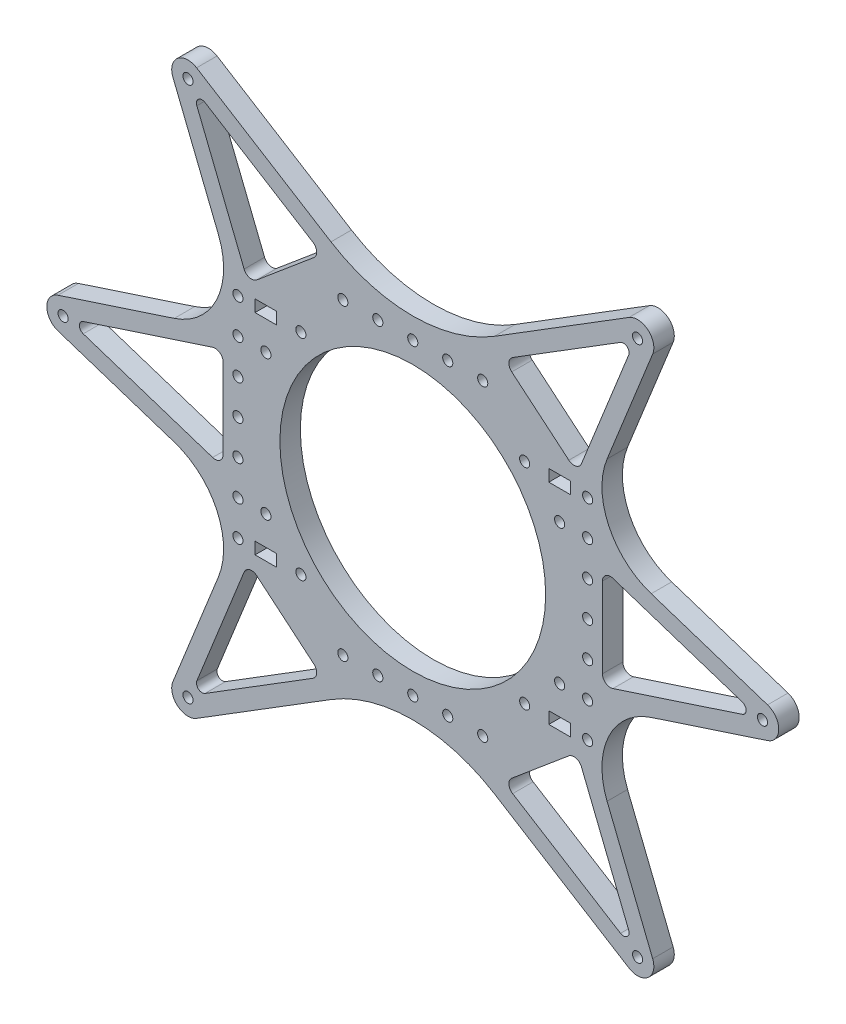
SolidWorks part; units mm, degrees
material "Acrylic (Medium-high impact)"
ref_plane "Front Plane" through (0, 0, 0) normal (0, 0, 1) x (1, 0, 0)
ref_plane "Top Plane" through (0, 0, 0) normal (0, 1, 0) x (1, 0, 0)
ref_plane "Right Plane" through (0, 0, 0) normal (1, 0, 0) x (0, 0, -1)
sketch "Sketch1" plane through (0, 0, 0) normal (0, 0, 1) x (1, 0, 0)
  line L0 (-447622.4345, 422.8828) -> (448935.6268, 422.8828) construction
  line L1 (587.9953, 497.7534) -> (601.0264, 465.2697)
  line L2 (698.5962, 452.8828) -> (698.5962, 392.8828) construction
  line L3 (653.3971, 419.0702) -> (-31485.9834, -37883.1519) construction
  line L4 (701.6962, 394.5828) -> (695.4962, 391.1828) construction
  line L5 (701.6962, 391.1828) -> (695.4962, 394.5828) construction
  line L6 (594.8522, 494.09) -> (608.3693, 460.3949)
  line L7 (594.7755, 503.4426) -> (633.2109, 479.5572)
  line L8 (597.1925, 496.0537) -> (628.0285, 476.8909)
  line L9 (594.8522, 494.09) -> (597.1925, 496.0537) construction
  line L10 (701.6962, 391.1828) -> (695.4962, 391.1828)
  line L11 (695.4962, 394.5828) -> (695.4962, 391.1828)
  line L12 (701.6962, 394.5828) -> (695.4962, 394.5828)
  line L13 (594.7755, 503.4426) -> (587.9953, 497.7534) construction
  line L14 (628.2915, 473.1954) -> (611.963, 459.4942)
  line L15 (608.3693, 460.3949) -> (628.0285, 476.8909) construction
  line L16 (701.6962, 394.5828) -> (701.6962, 391.1828)
  line L17 (-343.4038, 422.8828) -> (49656.5962, 422.8828) construction
  line L18 (648.8948, 432.061) -> (-31490.4849, 38734.2822) construction
  line L19 (-347.3366, 472.8828) -> (49652.6634, 472.8828) construction
  line L20 (-347.2527, 372.8828) -> (49652.7473, 372.8828) construction
  line L21 (562.3601, 421.3552) -> (599.3601, 409.2322)
  line L22 (602.3601, 434.3594) -> (602.3601, 411.4062)
  line L23 (555.1462, 427.3082) -> (555.1462, 418.4573) construction
  line L24 (562.3601, 424.4103) -> (599.3601, 436.5334)
  line L25 (599.3601, 409.2322) -> (599.3601, 436.5334) construction
  line L26 (555.1462, 427.3082) -> (588.4064, 438.2059)
  line L27 (562.3601, 421.3552) -> (562.3601, 424.4103) construction
  line L28 (555.1462, 418.4573) -> (588.4064, 407.5596)
  line L29 (594.8522, 351.6756) -> (608.3693, 385.3706)
  line L30 (594.7755, 342.3229) -> (633.2109, 366.2084)
  line L31 (611.963, 386.2714) -> (628.2915, 372.5702)
  line L32 (611.4962, 451.1828) -> (617.6962, 454.5828) construction
  line L33 (611.4962, 454.5828) -> (617.6962, 451.1828) construction
  line L34 (597.1925, 349.7118) -> (594.8522, 351.6756) construction
  line L35 (587.9953, 348.0122) -> (594.7755, 342.3229) construction
  line L36 (628.0285, 368.8746) -> (608.3693, 385.3706) construction
  line L37 (597.1925, 349.7118) -> (628.0285, 368.8746)
  line L38 (587.9953, 348.0122) -> (601.0264, 380.4959)
  line L39 (611.4962, 391.1828) -> (617.6962, 394.5828) construction
  line L40 (701.6962, 454.5828) -> (695.4962, 451.1828) construction
  line L41 (611.4962, 394.5828) -> (617.6962, 391.1828) construction
  line L42 (614.5962, 452.8828) -> (614.5962, 392.8828) construction
  line L43 (701.6962, 451.1828) -> (695.4962, 454.5828) construction
  line L44 (685.1639, 368.8746) -> (704.8231, 385.3706) construction
  line L45 (725.1971, 348.0122) -> (718.4169, 342.3229) construction
  line L46 (715.9998, 349.7118) -> (718.3402, 351.6756) construction
  line L47 (750.8323, 421.3552) -> (750.8323, 424.4103) construction
  line L48 (713.8323, 409.2322) -> (713.8323, 436.5334) construction
  line L49 (758.0462, 427.3082) -> (758.0462, 418.4573) construction
  line L50 (704.8231, 460.3949) -> (685.1639, 476.8909) construction
  line L51 (718.4169, 503.4426) -> (725.1971, 497.7534) construction
  line L52 (718.3402, 494.09) -> (715.9998, 496.0537) construction
  line L53 (611.4962, 454.5828) -> (617.6962, 454.5828)
  line L54 (617.6962, 451.1828) -> (617.6962, 454.5828)
  line L55 (611.4962, 451.1828) -> (617.6962, 451.1828)
  line L56 (701.6962, 451.1828) -> (701.6962, 454.5828)
  line L57 (701.6962, 451.1828) -> (695.4962, 451.1828)
  line L58 (695.4962, 451.1828) -> (695.4962, 454.5828)
  line L59 (701.6962, 454.5828) -> (695.4962, 454.5828)
  line L60 (725.1971, 348.0122) -> (712.166, 380.4959)
  line L61 (715.9998, 349.7118) -> (685.1639, 368.8746)
  line L62 (701.2294, 386.2714) -> (684.9009, 372.5702)
  line L63 (718.4169, 342.3229) -> (679.9814, 366.2084)
  line L64 (718.3402, 351.6756) -> (704.8231, 385.3706)
  line L65 (758.0462, 418.4573) -> (724.786, 407.5596)
  line L66 (758.0462, 427.3082) -> (724.786, 438.2059)
  line L67 (750.8323, 424.4103) -> (713.8323, 436.5334)
  line L68 (710.8323, 434.3594) -> (710.8323, 411.4062)
  line L69 (750.8323, 421.3552) -> (713.8323, 409.2322)
  line L70 (611.4962, 451.1828) -> (611.4962, 454.5828)
  line L71 (684.9009, 473.1954) -> (701.2294, 459.4942)
  line L72 (611.4962, 394.5828) -> (611.4962, 391.1828)
  line L73 (611.4962, 394.5828) -> (617.6962, 394.5828)
  line L74 (617.6962, 394.5828) -> (617.6962, 391.1828)
  line L75 (715.9998, 496.0537) -> (685.1639, 476.8909)
  line L76 (718.4169, 503.4426) -> (679.9814, 479.5572)
  line L77 (718.3402, 494.09) -> (704.8231, 460.3949)
  line L78 (725.1971, 497.7534) -> (712.166, 465.2697)
  line L79 (611.4962, 391.1828) -> (617.6962, 391.1828)
  line L80 (706.5962, 432.8828) -> (698.5962, 432.8828) construction
  line L81 (706.5962, 422.8828) -> (706.5962, 432.8828) construction
  line L82 (656.5962, 378.8828) -> (646.5962, 378.8828) construction
  line L83 (656.5962, 466.8828) -> (646.5962, 466.8828) construction
  line L84 (-50.5106, -284.224) -> (35304.8285, 35071.1151) construction
  line L85 (-50.5106, -284.224) -> (35304.8285, 35071.1151) construction
  line L86 (1363.703, -284.224) -> (-33991.6361, 35071.1151) construction
  line L111 (656.5962, -513.6368) -> (656.5962, 49486.3632) construction
  arc A0 (597.1925, 496.0537) -> (594.8522, 494.09) centre (596.3441, 494.6884) ccw
  arc A1 (587.9953, 497.7534) -> (594.7755, 503.4426) centre (592.3174, 499.4872) cw
  circle A2 centre (592.3174, 499.4872) radius 1.45
  arc A4 (608.3693, 460.3949) -> (611.963, 459.4942) centre (610.4925, 461.2467) ccw
  arc A5 (628.2915, 473.1954) -> (628.0285, 476.8909) centre (626.821, 474.9479) ccw
  circle A6 centre (592.3174, 499.4872) radius 4.6569 construction
  circle A7 centre (706.5962, 432.8828) radius 1.45
  circle A8 centre (706.5962, 442.8828) radius 1.45
  circle A9 centre (706.5962, 452.8828) radius 1.45
  circle A10 centre (706.5962, 392.8828) radius 1.45
  arc A11 (555.1462, 418.4573) -> (555.1462, 427.3082) centre (556.5962, 422.8828) cw
  circle A12 centre (556.5962, 422.8828) radius 1.45
  circle A13 centre (646.5962, 378.8828) radius 1.45
  circle A14 centre (556.5962, 422.8828) radius 4.6569 construction
  arc A15 (562.3601, 424.4103) -> (562.3601, 421.3552) centre (562.8606, 422.8828) ccw
  circle A16 centre (656.5962, 422.8828) radius 38
  circle A18 centre (636.5962, 378.8828) radius 1.45
  arc A19 (602.3601, 434.3594) -> (599.3601, 436.5334) centre (600.0724, 434.3594) ccw
  circle A20 centre (706.5962, 402.8828) radius 1.45
  arc A21 (599.3601, 409.2322) -> (602.3601, 411.4062) centre (600.0724, 411.4062) ccw
  circle A22 centre (656.5962, 466.8828) radius 1.45
  circle A24 centre (592.3174, 346.2783) radius 4.6569 construction
  arc A25 (628.0285, 368.8746) -> (628.2915, 372.5702) centre (626.821, 370.8177) ccw
  arc A27 (594.7755, 342.3229) -> (587.9953, 348.0122) centre (592.3174, 346.2783) cw
  arc A28 (594.8522, 351.6756) -> (597.1925, 349.7118) centre (596.3441, 351.0771) ccw
  arc A29 (611.963, 386.2714) -> (608.3693, 385.3706) centre (610.4925, 384.5189) ccw
  circle A31 centre (592.3174, 346.2783) radius 1.45
  circle A32 centre (706.5962, 412.8828) radius 1.45
  arc A33 (588.4064, 407.5596) -> (601.0264, 380.4959) centre (582.0351, 388.1144) cw
  circle A34 centre (656.5962, 378.8828) radius 1.45
  arc A35 (588.4064, 438.2059) -> (601.0264, 465.2697) centre (582.0351, 457.6512) ccw
  circle A37 centre (698.5962, 442.8828) radius 1.45
  circle A38 centre (698.5962, 402.8828) radius 1.45
  arc A39 (633.2109, 366.2084) -> (656.5962, 372.8828) centre (656.5962, 328.5778) cw
  arc A40 (633.2109, 479.5572) -> (656.5962, 472.8828) centre (656.5962, 517.1878) ccw
  circle A41 centre (720.8749, 346.2783) radius 4.6569 construction
  circle A42 centre (756.5962, 422.8828) radius 4.6569 construction
  circle A44 centre (646.5962, 466.8828) radius 1.45
  circle A45 centre (636.5962, 466.8828) radius 1.45
  circle A46 centre (720.8749, 499.4872) radius 4.6569 construction
  circle A48 centre (676.5962, 466.8828) radius 1.45
  circle A49 centre (666.5962, 466.8828) radius 1.45
  circle A50 centre (706.5962, 422.8828) radius 1.45
  arc A51 (679.9814, 479.5572) -> (656.5962, 472.8828) centre (656.5962, 517.1878) cw
  arc A52 (679.9814, 366.2084) -> (656.5962, 372.8828) centre (656.5962, 328.5778) ccw
  circle A53 centre (688.5962, 452.8828) radius 1.45
  circle A54 centre (688.5962, 392.8828) radius 1.45
  arc A55 (724.786, 438.2059) -> (712.166, 465.2697) centre (731.1572, 457.6512) cw
  arc A56 (724.786, 407.5596) -> (712.166, 380.4959) centre (731.1572, 388.1144) ccw
  circle A57 centre (624.5962, 392.8828) radius 1.45
  circle A58 centre (720.8749, 346.2783) radius 1.45
  arc A59 (701.2294, 386.2714) -> (704.8231, 385.3706) centre (702.6999, 384.5189) cw
  arc A60 (718.3402, 351.6756) -> (715.9998, 349.7118) centre (716.8483, 351.0771) cw
  arc A61 (718.4169, 342.3229) -> (725.1971, 348.0122) centre (720.8749, 346.2783) ccw
  arc A62 (685.1639, 368.8746) -> (684.9009, 372.5702) centre (686.3714, 370.8177) cw
  arc A63 (713.8323, 409.2322) -> (710.8323, 411.4062) centre (713.12, 411.4062) cw
  arc A64 (710.8323, 434.3594) -> (713.8323, 436.5334) centre (713.12, 434.3594) cw
  circle A65 centre (676.5962, 378.8828) radius 1.45
  arc A66 (750.8323, 424.4103) -> (750.8323, 421.3552) centre (750.3318, 422.8828) cw
  circle A67 centre (666.5962, 378.8828) radius 1.45
  circle A68 centre (756.5962, 422.8828) radius 1.45
  arc A69 (758.0462, 418.4573) -> (758.0462, 427.3082) centre (756.5962, 422.8828) ccw
  circle A70 centre (624.5962, 452.8828) radius 1.45
  circle A71 centre (606.5962, 422.8828) radius 1.45
  arc A74 (684.9009, 473.1954) -> (685.1639, 476.8909) centre (686.3714, 474.9479) cw
  arc A75 (704.8231, 460.3949) -> (701.2294, 459.4942) centre (702.6999, 461.2467) cw
  circle A76 centre (720.8749, 499.4872) radius 1.45
  arc A77 (725.1971, 497.7534) -> (718.4169, 503.4426) centre (720.8749, 499.4872) ccw
  arc A78 (715.9998, 496.0537) -> (718.3402, 494.09) centre (716.8483, 494.6884) cw
  circle A79 centre (614.5962, 402.8828) radius 1.45
  circle A80 centre (614.5962, 442.8828) radius 1.45
  circle A81 centre (606.5962, 412.8828) radius 1.45
  circle A83 centre (606.5962, 402.8828) radius 1.45
  circle A84 centre (606.5962, 392.8828) radius 1.45
  circle A85 centre (606.5962, 452.8828) radius 1.45
  circle A86 centre (606.5962, 442.8828) radius 1.45
  circle A87 centre (606.5962, 432.8828) radius 1.45
  circle A279 centre (626.5962, 466.8828) radius 1.45 [skipped]
  circle A282 centre (626.5962, 378.8828) radius 1.45 [skipped]
  circle A283 centre (698.5962, 422.8828) radius 1.45 [skipped]
  circle A284 centre (698.5962, 432.8828) radius 1.45 [skipped]
  circle A285 centre (698.5962, 412.8828) radius 1.45 [skipped]
  point P2 (620.1272, 466.3448)
  point P4 (604.6798, 472.924)
  point P5 (610.6788, 407.5004)
  point P6 (604.4937, 430.5743)
  point P7 (590.1096, 382.987)
  point P9 (656.5962, 422.8828)
  point P10 (592.2236, 451.9603)
  point P12 (560.2236, 451.9603)
  point P13 (615.5787, 412.0526)
  point P15 (596.4648, 452.5325)
  point P16 (593.7956, 519.1439)
  point P18 (562.0153, 451.7438)
  point P19 (589.324, 503.0546)
  point P21 (557.1601, 445.912)
  point P22 (691.7574, 496.0365)
  point P23 (586.2073, 519.1355)
  point P25 (698.5962, 452.8828)
  point P27 (593.4054, 384.161)
  point P31 (706.9167, 384.1702)
  point P32 (709.3005, 386.1481)
  point P33 (712.3266, 520.5499)
  point P34 (710.2125, 451.5766)
  point P37 (593.7956, 519.1439)
  point P38 (704.5328, 382.1922)
  point P40 (675.1867, 401.4708)
  point P41 (685.2778, 409.8289)
  point P43 (705.5495, 376.706)
  point P44 (637.2651, 404.097)
  point P46 (743.1543, 445.9191)
  point P47 (656.5962, 422.8828)
  point P48 (685.1467, 493.2598)
  point P49 (742.2125, 451.5766)
  point P53 (695.1768, 484.8286)
  point P55 (708.8884, 517.1528)
  point P56 (706.5155, 519.1439)
  point P57 (714.1038, 519.1355)
  point P64 (708.6406, 384.393)
  point P66 (665.171, 499.4399)
  point P67 (704.1427, 521.135)
  point P80 (602.3601, 422.8828)
  point P86 (499.5503, 435.3778)
  point P106 (620.1272, 379.4208)
  point P114 (563.3616, 328.8714)
  point P127 (698.5962, 422.8828)
  point P132 (656.5962, 460.8828)
  point P136 (656.5962, 465.4328)
  point P143 (704.687, 438.4721)
  point P145 (738.2906, 448.6533)
  point P146 (704.7346, 451.575)
  point P147 (738.2991, 451.7509)
  point P148 (738.3077, 454.8484)
  point P244 (749.8308, 328.8714)
  point P245 (693.0651, 379.4208)
  point P246 (710.8323, 422.8828)
  point P247 (698.5962, 422.8828)
  point P248 (723.8684, 503.0546)
  point P249 (693.0651, 466.3448)
  dimension "D2" = 2.9
  dimension "D3" = 6.2644
  dimension "D6" = 4
  dimension "D9" = 4
  dimension "D7" = 4
  dimension "D11" = 100
  dimension "D12" = 5
  dimension "D5" = 10
  dimension "D19" = 50
  dimension "D20" = 100
  dimension "D25" = 6.2644
  dimension "D13" = 3
  dimension "D15" = 37
  dimension "D18" = 42
  dimension "D23" = 10
  dimension "D28" = 10
  dimension "D39" = 3.4
  dimension "D37" = 2.9
  dimension "D38" = 76
  dimension "D40" = 4.55
  dimension "D8" = 50
  dimension "D10" = 30
  dimension "D14" = 50
  dimension "D16" = 37
  dimension "D17" = 2
  dimension "D21" = 44
  dimension "D22" = 35
  dimension "D24" = 5
  dimension "D26" = 3
  dimension "D27" = 8
  dimension "D29" = 5
  dimension "D30" = 6.2644
  dimension "D31" = 3
  dimension "D32" = 37
  dimension "D33" = 10
  dimension "D34" = 100
  dimension "D35" = 10
  dimension "D36" = 5
  dimension "D41" = 6.2
extrude "Boss-Extrude1" add sketch "Sketch1" along normal blind 5.85
